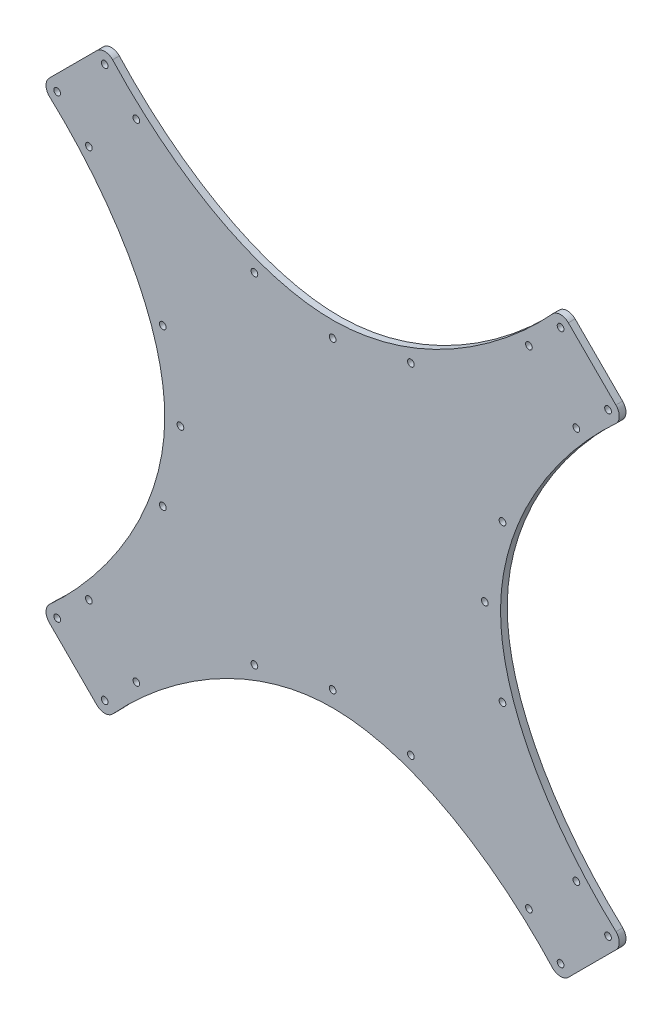
SolidWorks part; units mm, degrees
material "Zoltek Panex 33"
ref_plane "Front Plane" through (0, 0, 0) normal (0, 0, 1) x (1, 0, 0)
ref_plane "Top Plane" through (0, 0, 0) normal (0, 1, 0) x (1, 0, 0)
ref_plane "Right Plane" through (0, 0, 0) normal (1, 0, 0) x (0, 0, -1)
sketch "Sketch1" plane through (0, 0, 0) normal (0, 0, 1) x (1, 0, 0)
  line L17 (-70.8147, 145.9105) -> (-49.6015, 167.1237)
  line L18 (182.282, 145.9574) -> (161.0688, 167.1706)
  line L19 (-49.6015, -86.0205) -> (-70.8147, -64.8073)
  line L20 (161.1163, -86.0205) -> (182.3295, -64.8073)
  circle A5 centre (-12.2426, 40.5516) radius 1.5
  circle A6 centre (55.7574, 108.5516) radius 1.5
  circle A7 centre (123.7574, 40.5516) radius 1.5
  circle A8 centre (55.7574, -27.4484) radius 1.5
  circle A9 centre (131.6328, 75.5014) radius 1.5
  circle A10 centre (131.6328, 5.6019) radius 1.5
  circle A11 centre (20.8077, 116.427) radius 1.5
  circle A12 centre (90.7072, 116.427) radius 1.5
  circle A13 centre (-20.118, 75.5014) radius 1.5
  circle A14 centre (-20.118, 5.6019) radius 1.5
  circle A15 centre (20.8077, -35.3238) radius 1.5
  circle A16 centre (90.7072, -35.3238) radius 1.5
  circle A28 centre (-67.2792, 142.375) radius 1.5
  circle A29 centre (-46.066, 163.5882) radius 1.5
  circle A30 centre (157.5808, 163.5882) radius 1.5
  circle A32 centre (157.5808, -82.485) radius 1.5
  circle A33 centre (178.794, -61.2718) radius 1.5
  circle A34 centre (-67.2792, -61.2718) radius 1.5
  circle A35 centre (-46.066, -82.485) radius 1.5
  arc A36 (154.0453, 167.1237) -> (161.0688, 167.1706) centre (157.5808, 163.5882) cw
  arc A37 (-42.5304, 167.1237) -> (-49.6015, 167.1237) centre (-46.066, 163.5882) ccw
  arc A38 (-70.8147, 138.8395) -> (-70.8147, 145.9105) centre (-67.2792, 142.375) cw
  arc A40 (-70.8147, -57.7362) -> (-70.8147, -64.8073) centre (-67.2792, -61.2718) ccw
  arc A41 (-42.5304, -86.0205) -> (-49.6015, -86.0205) centre (-46.066, -82.485) cw
  arc A42 (154.0453, -86.0205) -> (161.1163, -86.0205) centre (157.5808, -82.485) ccw
  arc A43 (182.3295, -57.7362) -> (182.3295, -64.8073) centre (178.794, -61.2718) cw
  circle A44 centre (178.794, 142.375) radius 1.5
  arc A45 (182.3295, 138.8395) -> (182.282, 145.9574) centre (178.794, 142.375) ccw
  circle A46 centre (-53.137, 128.2329) radius 1.5
  circle A47 centre (-31.9238, 149.4461) radius 1.5
  circle A48 centre (143.4387, 149.4461) radius 1.5
  circle A49 centre (164.6519, 128.2329) radius 1.5
  circle A50 centre (143.4387, -68.3428) radius 1.5
  circle A51 centre (164.6519, -47.1296) radius 1.5
  circle A52 centre (-53.137, -47.1296) radius 1.5
  circle A53 centre (-31.9238, -68.3428) radius 1.5
  spline S0 degree 3 poles (-70.8147, 138.8395) (-44.2785, 114.5858) (5.7933, 40.5516) (-44.2785, -33.4826) (-70.8147, -57.7362) knots 0 0 0 0 0.5 1 1 1 1
  spline S1 degree 3 poles (-42.5304, 167.1237) (-18.2768, 140.5875) (55.7574, 90.5157) (129.7916, 140.5875) (154.0453, 167.1237) knots 0 0 0 0 0.5 1 1 1 1
  spline S2 degree 3 poles (-42.5304, -86.0205) (-18.2768, -59.4843) (55.7574, -9.4125) (129.7916, -59.4843) (154.0453, -86.0205) knots 0 0 0 0 0.5 1 1 1 1
  spline S3 degree 3 poles (182.3295, -57.7362) (155.7933, -33.4826) (105.7215, 40.5516) (155.7933, 114.5858) (182.3295, 138.8395) knots 0 0 0 0 0.5 1 1 1 1
  point P9 (55.7574, 40.5516)
  dimension "D7" = 3
  dimension "D8" = 5
  dimension "D9" = 3
  dimension "D10" = 5
  dimension "D16" = 3
  dimension "D18" = 3
  dimension "D20" = 3
  dimension "D22" = 3
  dimension "D25" = 3
  dimension "D28" = 3
  dimension "D33" = 3
  dimension "D34" = 3
  dimension "D17" = 3
  dimension "D29" = 3
  dimension "D36" = 3
  dimension "D37" = 3
  dimension "D4" = 5
  dimension "D11" = 3
  dimension "D12" = 20
  dimension "D13" = 20
  dimension "D14" = 3
  dimension "D15" = 3
  dimension "D19" = 3
  dimension "D21" = 3
  dimension "D24" = 3
  dimension "D26" = 3
  dimension "D31" = 3
  dimension "D32" = 3
  dimension "D39" = 3
  dimension "D40" = 3
  dimension "D43" = 3
  dimension "D44" = 3
  dimension "D5" = 30
  dimension "D6" = 30
  dimension "D23" = 5
  dimension "D27" = 20
  dimension "D30" = 20
  dimension "D35" = 20
  dimension "D38" = 20
  dimension "D41" = 20
  dimension "D42" = 20
extrude "Boss-Extrude2" add sketch "Sketch1" along normal blind 3 contours A14 | A15 | A8
